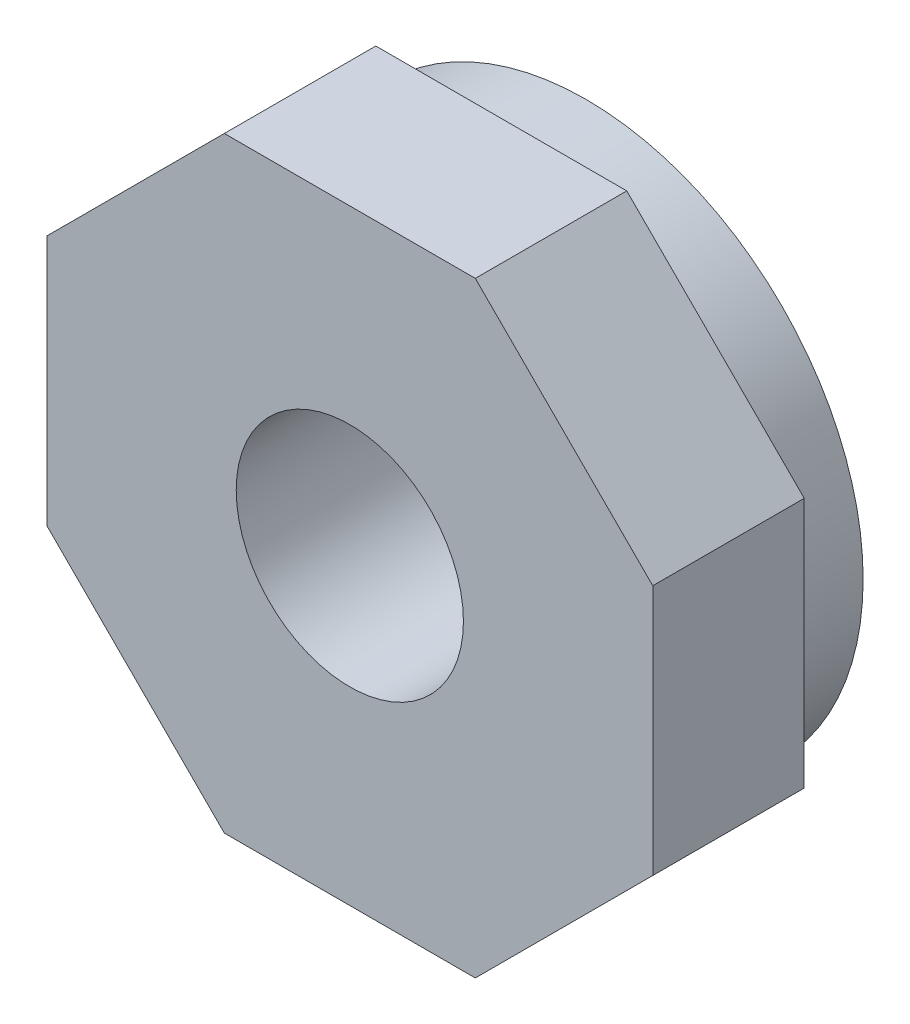
SolidWorks part; units mm, degrees
ref_plane "Front Plane" through (0, 0, 0) normal (0, 0, 1) x (1, 0, 0)
ref_plane "Top Plane" through (0, 0, 0) normal (0, 1, 0) x (1, 0, 0)
ref_plane "Right Plane" through (0, 0, 0) normal (1, 0, 0) x (0, 0, -1)
sketch "Sketch1" plane through (0, 0, 0) normal (0, 0, 1) x (1, 0, 0)
  line L0 (-1.3151, 3.175) -> (1.3151, 3.175)
  line L1 (1.3151, 3.175) -> (3.175, 1.3151)
  line L2 (3.175, 1.3151) -> (3.175, -1.3151)
  line L3 (3.175, -1.3151) -> (1.3151, -3.175)
  line L4 (1.3151, -3.175) -> (-1.3151, -3.175)
  line L5 (-1.3151, -3.175) -> (-3.175, -1.3151)
  line L6 (-3.175, -1.3151) -> (-3.175, 1.3151)
  line L7 (-3.175, 1.3151) -> (-1.3151, 3.175)
  circle A0 centre (0, 0) radius 1.1906
  circle A1 centre (0, 0) radius 3.175
  dimension "D3" = 2.3813
  dimension "D4" = 6.35
  dimension "D1" = 135
  dimension "D2" = 135
extrude "Boss-Extrude1" add sketch "Sketch1" along normal blind 1.5875 contours A1 A0 | A1 L0 L7 | A1 L1 L0 | A1 L2 L1 | A1 L3 L2 | A1 L4 L3 | A1 L5 L4 | A1 L6 L5 | A1 L7 L6
sketch "Sketch2" plane through (0, 0, 0) normal (0, 0, -1) x (-1, 0, 0)
  circle A0 centre (0, 0) radius 1.1906
  circle A1 centre (0, 0) radius 2.9032
extrude "Boss-Extrude2" add sketch "Sketch2" along normal blind 0.889
